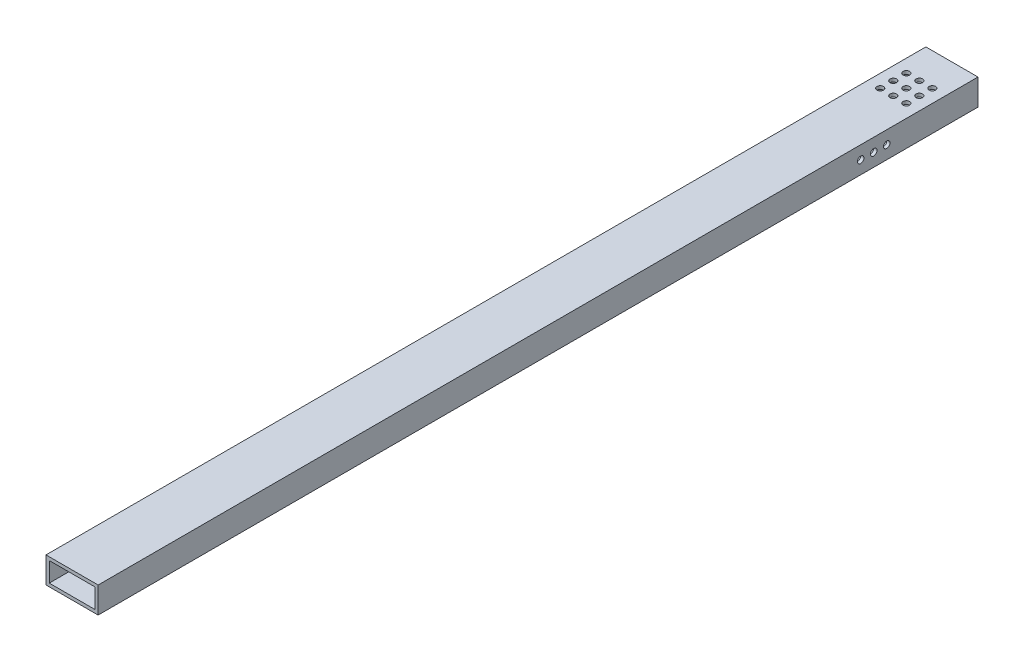
SolidWorks part; units mm, degrees
ref_plane "Front Plane" through (0, 0, 0) normal (0, 0, 1) x (1, 0, 0)
ref_plane "Top Plane" through (0, 0, 0) normal (0, 1, 0) x (1, 0, 0)
ref_plane "Right Plane" through (0, 0, 0) normal (1, 0, 0) x (0, 0, -1)
sketch "Sketch1" plane through (0, 0, 0) normal (0, 0, 1) x (1, 0, 0)
  line L0 (3.175, 22.225) -> (47.625, 22.225)
  line L1 (0, 0) -> (50.8, 0)
  line L2 (0, 0) -> (0, 25.4)
  line L3 (0, 25.4) -> (50.8, 25.4)
  line L4 (50.8, 0) -> (50.8, 25.4)
  line L5 (47.625, 3.175) -> (47.625, 22.225)
  line L6 (3.175, 3.175) -> (47.625, 3.175)
  line L7 (3.175, 3.175) -> (3.175, 22.225)
  dimension "D1" = 50.8
  dimension "D2" = 25.4
  dimension "D3" = 3.175
extrude "Boss-Extrude1" add sketch "Sketch1" along normal blind 857.25
sketch "Sketch2" plane through (50.8, 0, 0) normal (1, 0, 0) x (0, 0, -1)
  line L2 (0, 12.7) -> (-88.9, 12.7) construction
  line L3 (0, 0) -> (0, 25.4) construction
  circle A3 centre (-88.9, 12.7) radius 3.175
  circle A4 centre (-101.6, 12.7) radius 3.175
  circle A5 centre (-114.3, 12.7) radius 3.175
  dimension "D6" = 6.35
  dimension "D7" = 88.9
  dimension "D8" = 12.7
  dimension "D5" = 3
extrude "Cut-Extrude1" cut sketch "Sketch2" against normal through all both
sketch "Sketch3" plane through (0, 25.4, 0) normal (0, 1, 0) x (1, 0, 0)
  line L0 (12.7, 0) -> (12.7, -31.75) construction
  line L1 (50.8, 0) -> (0, 0) construction
  line L2 (12.7, -31.75) -> (0, -31.75) construction
  line L3 (0, -857.25) -> (0, 0) construction
  line L4 (12.7, -44.45) -> (12.7, -31.75) construction
  circle A0 centre (12.7, -31.75) radius 3.175
  circle A1 centre (25.4, -31.75) radius 3.175
  circle A2 centre (38.1, -31.75) radius 3.175
  circle A3 centre (25.4, -44.45) radius 3.175
  circle A4 centre (38.1, -44.45) radius 3.175
  circle A5 centre (25.4, -57.15) radius 3.175
  circle A6 centre (38.1, -57.15) radius 3.175
  circle A7 centre (12.7, -44.45) radius 3.175
  circle A8 centre (12.7, -57.15) radius 3.175
  dimension "D3" = 6.35
  dimension "D1" = 31.75
  dimension "D2" = 12.7
  dimension "D5" = 12.7
  dimension "D6" = 12.7
  dimension "D4" = 3
extrude "Cut-Extrude2" cut sketch "Sketch3" against normal through all both
